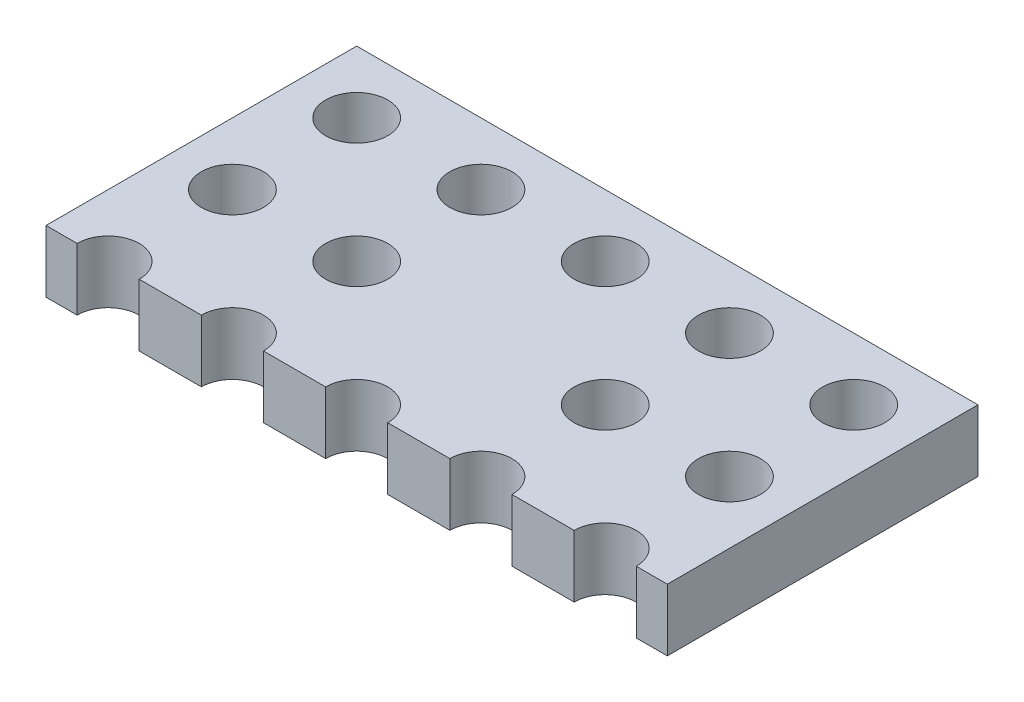
SolidWorks part; units mm, degrees
ref_plane "Front Plane" through (0, 0, 0) normal (0, 0, 1) x (1, 0, 0)
ref_plane "Top Plane" through (0, 0, 0) normal (0, 1, 0) x (1, 0, 0)
ref_plane "Right Plane" through (0, 0, 0) normal (1, 0, 0) x (0, 0, -1)
sketch "Sketch1" plane through (0, 0, 0) normal (0, 1, 0) x (1, 0, 0)
  line L1 (-50, -25) -> (50, -25)
  line L2 (-50, -25) -> (-50, 25)
  line L3 (-50, 25) -> (50, 25)
  line L4 (50, -25) -> (50, 25)
  line L5 (-50, -25) -> (50, 25) construction
  line L6 (-50, 25) -> (50, -25) construction
  point P0 (0, 0)
  dimension "D1" = 100
  dimension "D2" = 50
extrude "Boss-Extrude1" add sketch "Sketch1" along normal blind 10
sketch "Sketch2" plane through (0, 10, 0) normal (0, 1, 0) x (1, 0, 0)
  line L0 (50, 25) -> (-50, 25) construction
  line L1 (-50, 25) -> (-50, -25) construction
  line L2 (-50, 15) -> (50, 15) construction
  line L3 (50, -25) -> (50, 25) construction
  line L4 (-40, 25) -> (-40, -25) construction
  line L5 (-50, -25) -> (50, -25) construction
  line L6 (-40, 15) -> (-20, 15) construction
  circle A0 centre (-40, 15) radius 5
  circle A1 centre (-20, 15) radius 5
  circle A2 centre (0, 15) radius 5
  circle A3 centre (20, 15) radius 5
  circle A4 centre (40, 15) radius 5
  circle A5 centre (-40, -5) radius 5
  circle A6 centre (-20, -5) radius 5
  circle A7 centre (0, -5) radius 5
  circle A8 centre (20, -5) radius 5
  circle A9 centre (40, -5) radius 5
  dimension "D1" = 10
  dimension "D2" = 10
  dimension "D3" = 10
  dimension "D4" = 5
  dimension "D5" = 20
  dimension "D6" = 2
  dimension "D7" = 5
extrude "Cut-Extrude1" cut sketch "Sketch2" against normal blind 10 contours A0
pattern_linear "LPattern1" count 5 spacing 20 along (1, 0, 0) count 3 spacing 20 along (0, 0, 1) skipping (2, 1) of "Cut-Extrude1"
